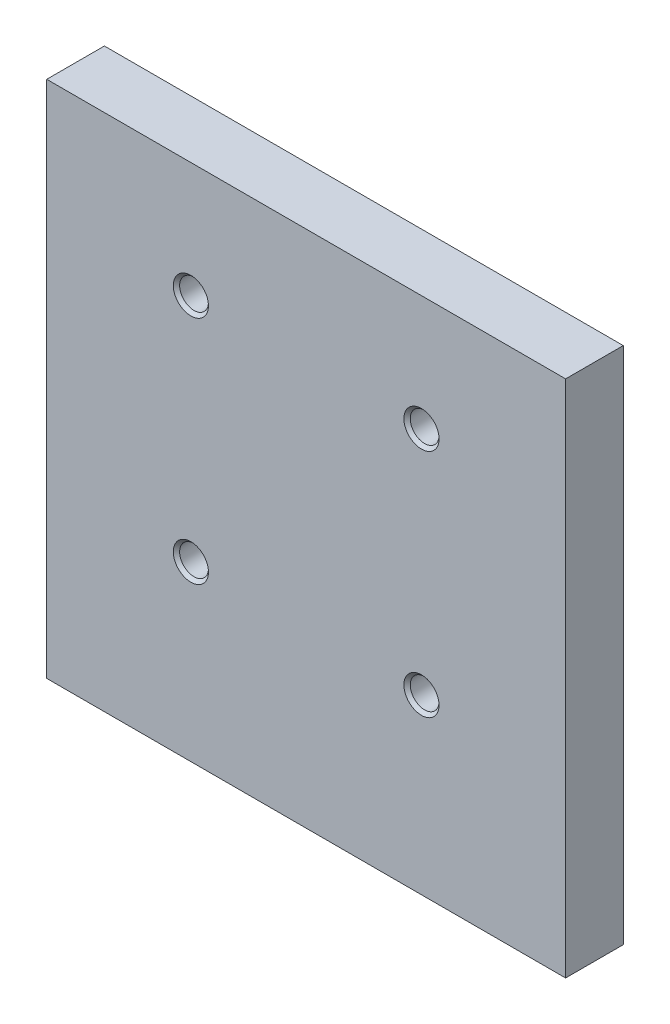
SolidWorks part; units mm, degrees
ref_plane "前视基准面" through (0, 0, 0) normal (0, 0, 1) x (1, 0, 0)
ref_plane "上视基准面" through (0, 0, 0) normal (0, 1, 0) x (1, 0, 0)
ref_plane "右视基准面" through (0, 0, 0) normal (1, 0, 0) x (0, 0, -1)
other "Configuration Table"
sketch "草图1" plane through (0, 0, 0) normal (0, 0, 1) x (1, 0, 0)
  line L0 (22.5, 45) -> (22.5, 0) construction
  line L1 (0, 0) -> (45, 0)
  line L2 (0, 0) -> (0, 45)
  line L3 (0, 45) -> (45, 45)
  line L4 (45, 0) -> (45, 45)
  circle A0 centre (12.5, 35) radius 1.6 construction
  circle A1 centre (32.5, 35) radius 1.6 construction
  circle A2 centre (32.5, 15) radius 1.6 construction
  circle A3 centre (12.5, 15) radius 1.6 construction
  point P14 (12.5, 35)
  dimension "D7" = 3.2
  dimension "D1" = 45
  dimension "D2" = 45
  dimension "D3" = 10
  dimension "D4" = 20
  dimension "D5" = 10
  dimension "D6" = 20
extrude "凸台-拉伸1" add sketch "草图1" along normal blind 5
sketch "草图2" plane through (0, 0, 5) normal (0, 0, 1) x (1, 0, 0)
  line L0 (22.5, 0) -> (22.5, 45) construction
  line L1 (0, 0) -> (45, 0) construction
  line L2 (45, 45) -> (0, 45) construction
  point P0 (12.5, 35)
  point P1 (32.5, 35)
  point P2 (32.5, 15)
  point P4 (12.5, 15)
  point P6 (0, 0)
  point P15 (14.3728, 35.7613)
  point P16 (11.9696, 41.7038)
  point P17 (52.6057, 30.8238)
  point P18 (37.7932, 45)
  point P19 (52.0376, 11.3797)
  point P20 (53.4359, 19.4632)
  point P21 (14.7223, 16.5794)
  dimension "D1" = 10
  dimension "D2" = 10
  dimension "D3" = 10
  dimension "D4" = 10
  dimension "D5" = 20
  dimension "D6" = 10
  dimension "D7" = 30
  dimension "D8" = 10
hole_wizard "M3 螺纹孔3" positions "草图2" profile "草图7" tap size "M3" standard "GB" end condition through all
sketch "草图7" plane through (12.5, 35, 5) normal (1, 0, 0) x (0, -1, 0)
  line L0 (0, 0) -> (0, 5)
  line L1 (0, 5) -> (1.25, 5)
  line L2 (1.25, 5) -> (1.25, 0.275)
  line L3 (1.25, 0.275) -> (1.525, 0)
  line L5 (1.525, 0) -> (0, 0)
  line L6 (-1.25, 0.275) -> (-1.525, 0) construction
  line L11 (0, -6.35) -> (0, 107.95) construction
  dimension "通孔螺纹孔钻头直径" = 2.5
  dimension "通孔螺纹孔钻头深度" = 5
  dimension "近端锥形沉头孔直径" = 3.05
  dimension "近端锥形沉头孔角度" = 90
cosmetic thread "孔螺纹线1" parameters "D2"=3
cosmetic thread "孔螺纹线2" parameters "D2"=3
cosmetic thread "孔螺纹线3" parameters "D2"=3
cosmetic thread "孔螺纹线4" parameters "D2"=3
